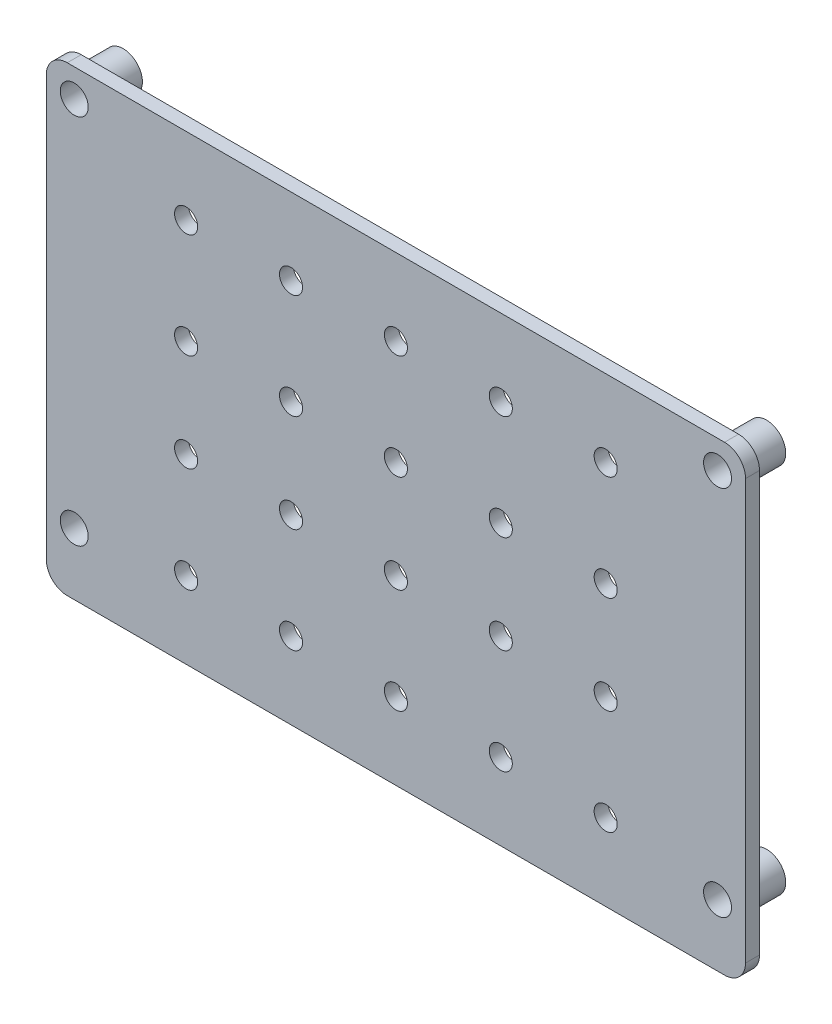
SolidWorks part; units mm, degrees
ref_plane "Front Plane" through (0, 0, 0) normal (0, 0, 1) x (1, 0, 0)
ref_plane "Top Plane" through (0, 0, 0) normal (0, 1, 0) x (1, 0, 0)
ref_plane "Right Plane" through (0, 0, 0) normal (1, 0, 0) x (0, 0, -1)
sketch "Sketch1" plane through (0, 0, 0) normal (0, 0, 1) x (1, 0, 0)
  line L0 (10, -35) -> (10, 1) construction
  line L1 (-50, 33) -> (50, 33)
  line L2 (-50, 33) -> (-50, -33)
  line L3 (-50, -33) -> (50, -33)
  line L4 (50, 33) -> (50, -33)
  line L5 (0, -33) -> (0, 33) construction
  circle A0 centre (-46, 29) radius 2
  circle A1 centre (46, 29) radius 2
  circle A2 centre (-46, -24.15) radius 2
  circle A3 centre (46, -24.15) radius 2
  point P17 (0, 0)
  point P18 (0, 0)
  point P19 (0, 0)
  point P20 (-47, -21.15)
  point P21 (-47, -21.15)
  point P22 (-47, -21.15)
  point P23 (0, 0)
  point P24 (-47, -21.15)
  point P25 (0, 0)
  point P26 (0, 0)
  dimension "D3" = 4
  dimension "D1" = 100
  dimension "D2" = 66
  dimension "D4" = 92
  dimension "D5" = 4
  dimension "D6" = 4
  dimension "D7" = 53.15
  dimension "D8" = 10
extrude "Boss-Extrude1" add sketch "Sketch1" along normal blind 2
fillet "Fillet1" radius 3 4 edges at (-50, 33, 1) (-50, -33, 1) (50, -33, 1) (50, 33, 1)
sketch "Sketch2" plane through (0, 0, 2) normal (0, 0, 1) x (1, 0, 0)
  line L0 (-47, -33) -> (47, -33) construction
  line L1 (50, -30) -> (50, 30) construction
  circle A0 centre (0, -22) radius 1.65
  circle A1 centre (0, -7) radius 1.65
  point P7 (0, 0)
  point P20 (0, 0)
  dimension "D2" = 3.3
  dimension "D3" = 50
  dimension "D5" = 15
  dimension "D1" = 11
extrude "Cut-Extrude1" cut sketch "Sketch2" against normal up to next
pattern_linear "LPattern1" count 3 spacing 15 along (-1, 0, 0) count 3 spacing 15 along (1, 0, 0) of "Cut-Extrude1"
mirror "Mirror1" about plane through (0, 0, 0) normal (0, 1, 0) of "LPattern1", "Cut-Extrude1"
sketch "Sketch4" plane through (0, 0, 0) normal (0, 0, -1) x (-1, 0, 0)
  circle A0 centre (-46, 29) radius 2.75
  circle A1 centre (-46, -24.15) radius 2.75
  circle A2 centre (46, -24.15) radius 2.75
  circle A3 centre (46, 29) radius 2.75
  circle A4 centre (46, 29) radius 2 construction
  circle A5 centre (46, -24.15) radius 2 construction
  circle A6 centre (-46, -24.15) radius 2 construction
  circle A7 centre (-46, 29) radius 2 construction
  circle A8 centre (46, 29) radius 2
  circle A9 centre (46, -24.15) radius 2
  circle A10 centre (-46, -24.15) radius 2
  circle A11 centre (-46, 29) radius 2
  dimension "D1" = 5.5
extrude "Boss-Extrude2" add sketch "Sketch4" along normal blind 5
